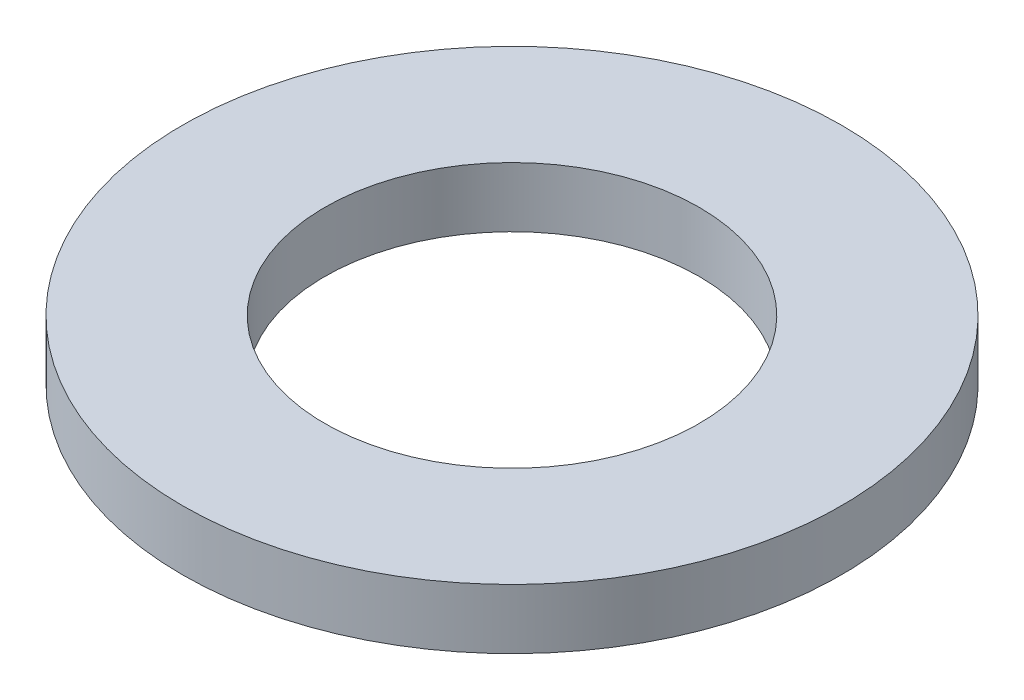
SolidWorks part; units mm, degrees
material "不锈钢"
ref_plane "基准面1" through (0, 0, 0) normal (0, 0, 1) x (1, 0, 0)
ref_plane "基准面2" through (0, 0, 0) normal (0, 1, 0) x (1, 0, 0)
ref_plane "基准面3" through (0, 0, 0) normal (1, 0, 0) x (0, 0, -1)
sketch "尺寸草图" plane through (0, 0, 0) normal (0, 0, 1) x (1, 0, 0)
  line L0 (0, 0) -> (9.1, 0)
  point P3 (4, 0)
  point P4 (44, 0)
  point P5 (25, 0)
  dimension "h" = 4
  dimension "d2" = 44
  dimension "d1" = 25
sketch "草图1" plane through (0, 0, 0) normal (0, 0, 1) x (1, 0, 0)
  line L0 (0, 0) -> (0, 52.7318) construction
  line L2 (-12.5, 8.6445) -> (-22, 8.6445)
  line L3 (-12.5, 8.6445) -> (-12.5, 12.6445)
  line L4 (-12.5, 12.6445) -> (-22, 12.6445)
  line L5 (-22, 8.6445) -> (-22, 12.6445)
  dimension "h" = 4
  dimension "D1" = 12.5
  dimension "D2" = 22
revolve "基体-旋转" add sketch "草图1" angle 360 about L0
equation "\"h@草图1\" = \"h@尺寸草图\""
equation "\"D1@草图1\" = \"d1@尺寸草图\" / 2"
equation "\"D2@草图1\" = \"d2@尺寸草图\" / 2"
